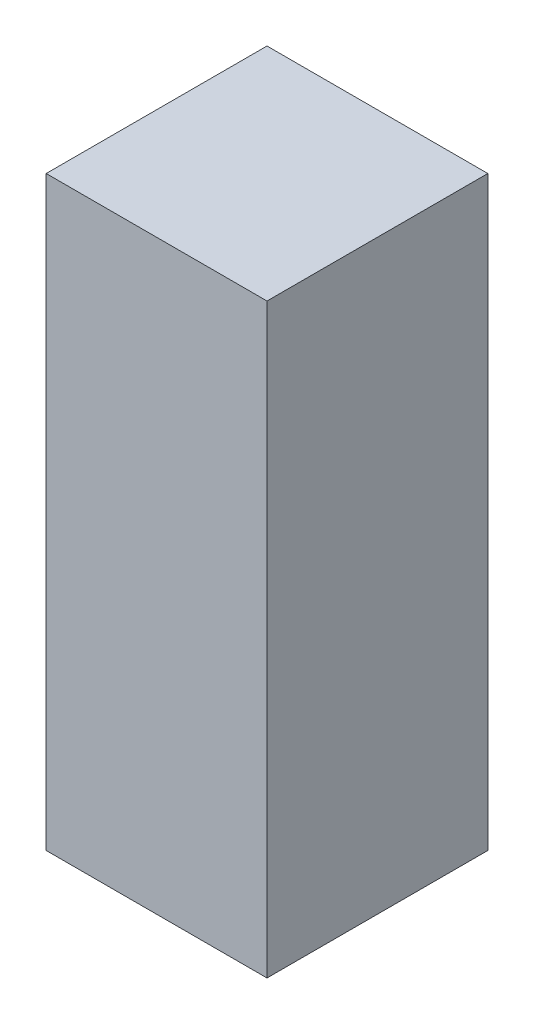
SolidWorks part; units mm, degrees
ref_plane "Front Plane" through (0, 0, 0) normal (0, 0, 1) x (1, 0, 0)
ref_plane "Top Plane" through (0, 0, 0) normal (0, 1, 0) x (1, 0, 0)
ref_plane "Right Plane" through (0, 0, 0) normal (1, 0, 0) x (0, 0, -1)
sketch "Sketch1" plane through (0, 0, 0) normal (0, 1, 0) x (1, 0, 0)
  line L1 (-25.4, -25.4) -> (25.4, -25.4)
  line L2 (-25.4, -25.4) -> (-25.4, 25.4)
  line L3 (-25.4, 25.4) -> (25.4, 25.4)
  line L4 (25.4, -25.4) -> (25.4, 25.4)
  line L5 (-25.4, -25.4) -> (25.4, 25.4) construction
  line L6 (-25.4, 25.4) -> (25.4, -25.4) construction
  point P0 (0, 0)
  dimension "D1" = 50.8
  dimension "D2" = 50.8
extrude "Boss-Extrude1" add sketch "Sketch1" along normal blind 134.874
